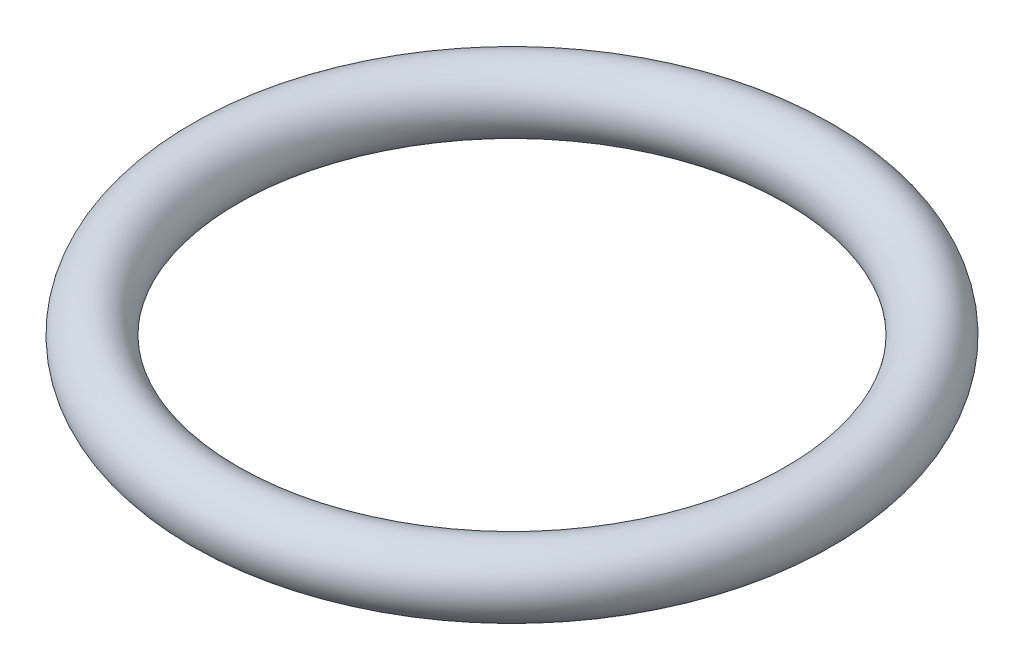
SolidWorks part; units mm, degrees
ref_plane "Front Plane" through (0, 0, 0) normal (0, 0, 1) x (1, 0, 0)
ref_plane "Top Plane" through (0, 0, 0) normal (0, 1, 0) x (1, 0, 0)
ref_plane "Right Plane" through (0, 0, 0) normal (1, 0, 0) x (0, 0, -1)
other "Configuration Table"
sketch "Sketch1" plane through (0, 0, 0) normal (0, 1, 0) x (1, 0, 0)
  circle A0 centre (0, 0) radius 14.15
sweep "Sweep1" add path "Sketch1" circular profile diameter 3.1 parameters "D3"=3.1
